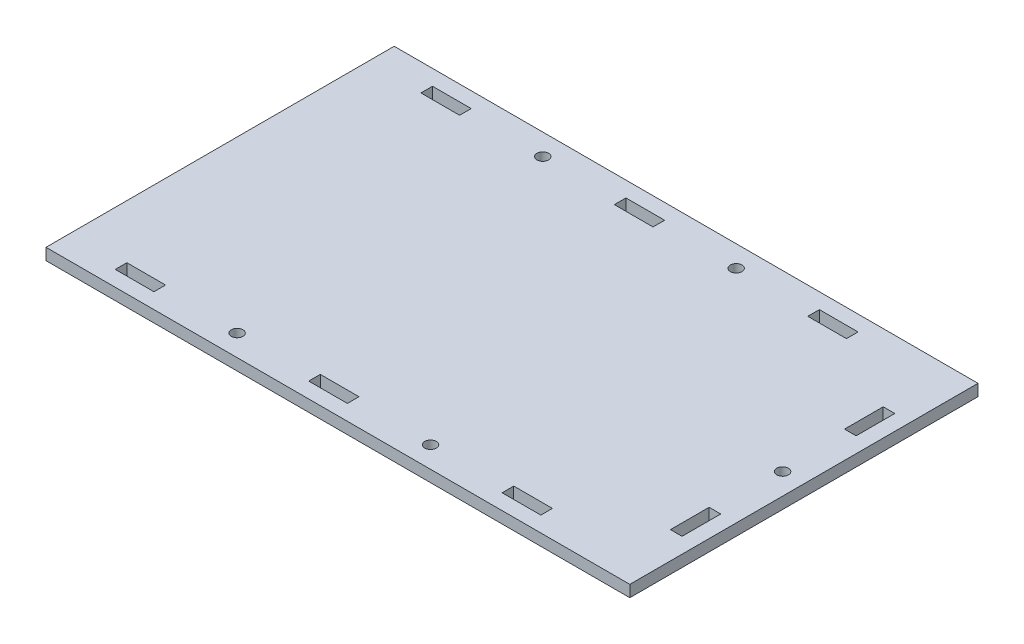
SolidWorks part; units mm, degrees
ref_plane "Front Plane" through (0, 0, 0) normal (0, 0, 1) x (1, 0, 0)
ref_plane "Top Plane" through (0, 0, 0) normal (0, 1, 0) x (1, 0, 0)
ref_plane "Right Plane" through (0, 0, 0) normal (1, 0, 0) x (0, 0, -1)
sketch "Sketch1" plane through (0, 0, 0) normal (0, 1, 0) x (1, 0, 0)
  line L0 (-27, 86) -> (-27, 83)
  line L1 (0, 0) -> (-150.9, 0)
  line L2 (0, 0) -> (0, 90)
  line L3 (0, 90) -> (-150.9, 90)
  line L4 (-150.9, 0) -> (-150.9, 90)
  line L5 (-27, 86) -> (-37, 86)
  line L6 (0, 45) -> (-150.9, 45) construction
  line L7 (-75.45, 90) -> (-75.45, 0) construction
  line L8 (-27, 83) -> (-37, 83)
  line L9 (-37, 83) -> (-37, 86)
  line L10 (-77, 86) -> (-87, 86)
  line L11 (-77, 86) -> (-77, 83)
  line L12 (-77, 83) -> (-87, 83)
  line L13 (-87, 83) -> (-87, 86)
  line L14 (-127, 86) -> (-137, 86)
  line L15 (-137, 86) -> (-137, 83)
  line L16 (-137, 83) -> (-127, 83)
  line L17 (-127, 83) -> (-127, 86)
  line L18 (-137, 4) -> (-137, 7)
  line L19 (-127, 4) -> (-137, 4)
  line L20 (-127, 7) -> (-127, 4)
  line L21 (-137, 7) -> (-127, 7)
  line L22 (-87, 7) -> (-87, 4)
  line L23 (-77, 4) -> (-77, 7)
  line L24 (-77, 4) -> (-87, 4)
  line L25 (-77, 7) -> (-87, 7)
  line L26 (-37, 7) -> (-37, 4)
  line L27 (-27, 4) -> (-37, 4)
  line L28 (-27, 4) -> (-27, 7)
  line L29 (-27, 7) -> (-37, 7)
  line L30 (-4, 72.5) -> (-7, 72.5)
  line L31 (-7, 27.5) -> (-4, 27.5)
  line L32 (-7, 72.5) -> (-7, 62.5)
  line L33 (-4, 62.5) -> (-4, 72.5)
  line L34 (-7, 62.5) -> (-4, 62.5)
  line L35 (-7, 17.5) -> (-7, 27.5)
  line L36 (-4, 17.5) -> (-7, 17.5)
  line L37 (-4, 27.5) -> (-4, 17.5)
  line L38 (-5.5, 62.5) -> (-5.5, 27.5) construction
  circle A0 centre (-57, 84.5) radius 1.5
  circle A1 centre (-107, 84.5) radius 1.5
  circle A2 centre (-107, 5.5) radius 1.5
  circle A3 centre (-57, 5.5) radius 1.5
  circle A4 centre (-5.5, 45) radius 1.5
  point P13 (-27, 86)
  point P14 (-37, 84.5)
  point P20 (-77, 86)
  dimension "D9" = 40
  dimension "D8" = 3
  dimension "D1" = 150.9
  dimension "D2" = 90
  dimension "D3" = 27
  dimension "D4" = 4
  dimension "D5" = 10
  dimension "D6" = 3
  dimension "D7" = 20
  dimension "D10" = 20
  dimension "D11" = 13.9
  dimension "D12" = 17.5
  dimension "D13" = 4
extrude "Boss-Extrude1" add sketch "Sketch1" along normal blind 3
